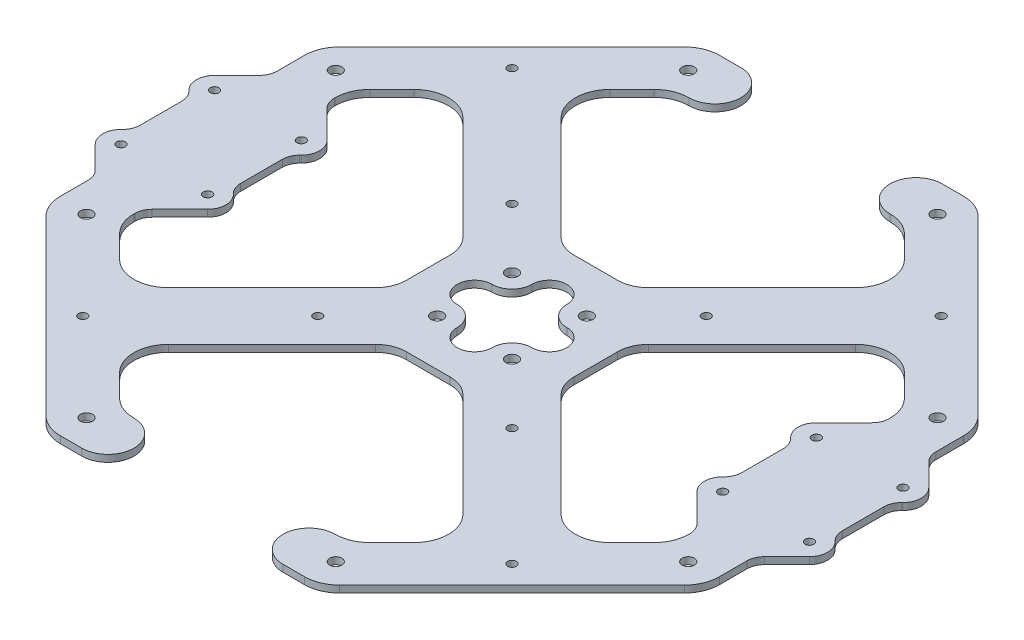
SolidWorks part; units mm, degrees
material "Hexcel AS4C (3000 Filaments)"
ref_plane "Front Plane" through (0, 0, 0) normal (0, 0, 1) x (1, 0, 0)
ref_plane "Top Plane" through (0, 0, 0) normal (0, 1, 0) x (1, 0, 0)
ref_plane "Right Plane" through (0, 0, 0) normal (1, 0, 0) x (0, 0, -1)
sketch "Sketch2" plane through (0, 0, 0) normal (0, 1, 0) x (1, 0, 0)
  line L0 (42.4264, 70.7107) -> (36.066, 77.0711)
  line L1 (92.0711, 42.2792) -> (42.2792, 92.0711)
  line L2 (35.2082, 95) -> (-35.2082, 95)
  line L3 (-42.2792, 92.0711) -> (-92.0711, 42.2792)
  line L5 (-92.0711, -42.2792) -> (-42.2792, -92.0711)
  line L6 (-35.2082, -95) -> (35.2082, -95)
  line L7 (42.2792, -92.0711) -> (92.0711, -42.2792)
  line L8 (95, 27.2345) -> (95, 35.2082)
  line L9 (28.9949, 80) -> (-28.9949, 80)
  line L10 (-70.7107, 42.4264) -> (-77.0711, 36.066)
  line L12 (-42.4264, -70.7107) -> (-36.066, -77.0711)
  line L13 (-28.9949, -80) -> (28.9949, -80)
  line L14 (70.7107, -42.4264) -> (77.0711, -36.066)
  line L68 (-80, 33.1371) -> (-80, -33.1371) construction
  line L69 (-80, -33.1371) -> (-33.1371, -80) construction
  line L70 (-33.1371, -80) -> (33.1371, -80) construction
  line L71 (33.1371, -80) -> (80, -33.1371) construction
  line L72 (80, -33.1371) -> (80, 33.1371) construction
  line L73 (80, 33.1371) -> (33.1371, 80) construction
  line L74 (33.1371, 80) -> (-33.1371, 80) construction
  line L75 (-33.1371, 80) -> (-80, 33.1371) construction
  line L76 (-95, 39.3503) -> (-95, -39.3503) construction
  line L77 (-95, -39.3503) -> (-39.3503, -95) construction
  line L78 (-39.3503, -95) -> (39.3503, -95) construction
  line L79 (39.3503, -95) -> (95, -39.3503) construction
  line L80 (95, -39.3503) -> (95, 39.3503) construction
  line L81 (95, 39.3503) -> (39.3503, 95) construction
  line L82 (39.3503, 95) -> (-39.3503, 95) construction
  line L83 (-39.3503, 95) -> (-95, 39.3503) construction
  line L84 (-26.7774, 12.6353) -> (-56.5685, 42.4264)
  line L93 (-12.6353, 26.7774) -> (-42.4264, 56.5685)
  line L94 (26.7774, 12.6353) -> (56.5685, 42.4264)
  line L95 (12.6353, 26.7774) -> (42.4264, 56.5685)
  line L96 (12.6353, -26.7774) -> (42.4264, -56.5685)
  line L97 (26.7774, -12.6353) -> (56.5685, -42.4264)
  line L98 (-26.7774, -12.6353) -> (-56.5685, -42.4264)
  line L99 (-12.6353, -26.7774) -> (-42.4264, -56.5685)
  line L100 (-6.2731, 24.1421) -> (6.2731, 24.1421)
  line L101 (24.1421, 6.2731) -> (24.1421, -6.2731)
  line L102 (6.2731, -24.1421) -> (-6.2731, -24.1421)
  line L103 (-24.1421, -6.2731) -> (-24.1421, 6.2731)
  line L104 (-36.066, 77.0711) -> (-42.4264, 70.7107)
  line L105 (77.0711, 36.066) -> (70.7107, 42.4264)
  line L106 (36.066, -77.0711) -> (42.4264, -70.7107)
  line L107 (-77.0711, -36.066) -> (-70.7107, -42.4264)
  line L115 (97, 15.5) -> (99.2388, 15.5)
  line L116 (80, 28.9949) -> (80, 28.7569)
  line L118 (74.2388, 15.5) -> (78, 15.5)
  line L120 (72.2388, 6.0043) -> (72.2388, -6.0043)
  line L131 (-95, 35.2082) -> (-95, -35.2082) [skipped]
  line L132 (101.2388, 6.0043) -> (101.2388, -6.0043)
  line L133 (102.9511, 17.2123) -> (96.4645, 23.699)
  line L134 (95, -27.2345) -> (95, -35.2082)
  line L135 (70.5265, 17.2123) -> (78.5355, 25.2214)
  line L136 (102.9511, 9.7877) -> (102.7033, 9.5398)
  line L137 (70.5265, -9.7877) -> (70.7743, -9.5398)
  line L138 (70.5265, 9.7877) -> (70.7743, 9.5398)
  line L139 (102.9511, -9.7877) -> (102.7033, -9.5398)
  line L140 (70.5265, -17.2123) -> (78.5355, -25.2214)
  line L141 (102.9511, -17.2123) -> (96.4645, -23.699)
  line L142 (74.2388, -15.5) -> (78, -15.5)
  line L143 (80, -28.9949) -> (80, -28.7569)
  line L144 (97, -15.5) -> (99.2388, -15.5)
  line L145 (-95, -27.2345) -> (-95, -35.2082)
  line L146 (-95, 27.2345) -> (-95, 35.2082)
  line L147 (-97, -15.5) -> (-99.2388, -15.5)
  line L148 (-80, -28.9949) -> (-80, -28.7569)
  line L149 (-74.2388, -15.5) -> (-78, -15.5)
  line L150 (-102.9511, -17.2123) -> (-96.4645, -23.699)
  line L151 (-70.5265, -17.2123) -> (-78.5355, -25.2214)
  line L152 (-102.9511, -9.7877) -> (-102.7033, -9.5398)
  line L153 (-70.5265, 9.7877) -> (-70.7743, 9.5398)
  line L154 (-70.5265, -9.7877) -> (-70.7743, -9.5398)
  line L155 (-102.9511, 9.7877) -> (-102.7033, 9.5398)
  line L156 (-70.5265, 17.2123) -> (-78.5355, 25.2214)
  line L157 (-102.9511, 17.2123) -> (-96.4645, 23.699)
  line L158 (-74.2388, 15.5) -> (-78, 15.5)
  line L159 (-80, 28.9949) -> (-80, 28.7569)
  line L160 (-97, 15.5) -> (-99.2388, 15.5)
  line L161 (-101.2388, 6.0043) -> (-101.2388, -6.0043)
  line L162 (-72.2388, 6.0043) -> (-72.2388, -6.0043)
  line L163 (-5.0334, 10.7834) -> (-5.0334, 14.3954)
  line L164 (-10.7834, 5.0334) -> (-14.3954, 5.0334)
  line L166 (-10.7834, -5.0334) -> (-14.3954, -5.0334)
  line L168 (-5.0334, -10.7834) -> (-5.0334, -14.3954)
  line L170 (5.0334, -10.7834) -> (5.0334, -14.3954)
  line L172 (10.7834, -5.0334) -> (14.3954, -5.0334)
  line L174 (10.7834, 5.0334) -> (14.3954, 5.0334)
  line L176 (5.0334, 10.7834) -> (5.0334, 14.3954)
  arc A0 (95, -27.2345) -> (96.4645, -23.699) centre (100, -27.2345) cw
  arc A2 (-80, -28.9949) -> (-77.0711, -36.066) centre (-70, -28.9949) ccw
  arc A3 (-36.066, -77.0711) -> (-28.9949, -80) centre (-28.9949, -70) ccw
  arc A4 (28.9949, -80) -> (36.066, -77.0711) centre (28.9949, -70) ccw
  arc A5 (77.0711, -36.066) -> (80, -28.9949) centre (70, -28.9949) ccw
  arc A6 (77.0711, 36.066) -> (80, 28.9949) centre (70, 28.9949) cw
  arc A7 (36.066, 77.0711) -> (28.9949, 80) centre (28.9949, 70) ccw
  arc A8 (-28.9949, 80) -> (-36.066, 77.0711) centre (-28.9949, 70) ccw
  arc A9 (-77.0711, 36.066) -> (-80, 28.9949) centre (-70, 28.9949) ccw
  arc A10 (-95, -35.2082) -> (-92.0711, -42.2792) centre (-85, -35.2082) ccw
  arc A11 (-42.2792, -92.0711) -> (-35.2082, -95) centre (-35.2082, -85) ccw
  arc A12 (35.2082, -95) -> (42.2792, -92.0711) centre (35.2082, -85) ccw
  arc A13 (92.0711, -42.2792) -> (95, -35.2082) centre (85, -35.2082) ccw
  arc A14 (92.0711, 42.2792) -> (95, 35.2082) centre (85, 35.2082) cw
  arc A15 (42.2792, 92.0711) -> (35.2082, 95) centre (35.2082, 85) ccw
  arc A16 (-35.2082, 95) -> (-42.2792, 92.0711) centre (-35.2082, 85) ccw
  arc A17 (-92.0711, 42.2792) -> (-95, 35.2082) centre (-85, 35.2082) ccw
  arc A18 (-42.4264, -70.7107) -> (-42.4264, -56.5685) centre (-35.3553, -63.6396) cw
  arc A19 (70.7107, -42.4264) -> (56.5685, -42.4264) centre (63.6396, -35.3553) cw
  arc A20 (42.4264, 70.7107) -> (42.4264, 56.5685) centre (35.3553, 63.6396) cw
  arc A21 (-70.7107, 42.4264) -> (-56.5685, 42.4264) centre (-63.6396, 35.3553) cw
  arc A22 (-56.5685, -42.4264) -> (-70.7107, -42.4264) centre (-63.6396, -35.3553) cw
  arc A23 (42.4264, -56.5685) -> (42.4264, -70.7107) centre (35.3553, -63.6396) cw
  arc A24 (56.5685, 42.4264) -> (70.7107, 42.4264) centre (63.6396, 35.3553) cw
  arc A25 (-42.4264, 56.5685) -> (-42.4264, 70.7107) centre (-35.3553, 63.6396) cw
  arc A26 (-12.6353, -26.7774) -> (-6.2731, -24.1421) centre (-6.2731, -33.1396) cw
  arc A27 (12.6353, -26.7774) -> (6.2731, -24.1421) centre (6.2731, -33.1396) ccw
  arc A28 (26.7774, -12.6353) -> (24.1421, -6.2731) centre (33.1396, -6.2731) cw
  arc A29 (26.7774, 12.6353) -> (24.1421, 6.2731) centre (33.1396, 6.2731) ccw
  arc A30 (12.6353, 26.7774) -> (6.2731, 24.1421) centre (6.2731, 33.1396) cw
  arc A31 (-12.6353, 26.7774) -> (-6.2731, 24.1421) centre (-6.2731, 33.1396) ccw
  arc A32 (-26.7774, -12.6353) -> (-24.1421, -6.2731) centre (-33.1396, -6.2731) ccw
  arc A33 (-26.7774, 12.6353) -> (-24.1421, 6.2731) centre (-33.1396, 6.2731) cw
  circle A34 centre (-86.7388, 35.9284) radius 1.75
  circle A35 centre (-35.9284, 86.7388) radius 1.75
  circle A36 centre (35.9284, 86.7388) radius 1.75
  circle A37 centre (86.7388, 35.9284) radius 1.75
  circle A38 centre (86.7388, -35.9284) radius 1.75
  circle A39 centre (35.9284, -86.7388) radius 1.75
  circle A40 centre (-35.9284, -86.7388) radius 1.75
  circle A41 centre (-86.7388, -35.9284) radius 1.75
  circle A42 centre (10.7834, 10.7834) radius 1.75
  circle A43 centre (10.7834, -10.7834) radius 1.75
  circle A44 centre (-10.7834, -10.7834) radius 1.75
  circle A45 centre (-10.7834, 10.7834) radius 1.75
  circle A55 centre (-28, 28) radius 1.25
  circle A56 centre (-61.8718, 61.8718) radius 1.25
  circle A57 centre (61.8718, 61.8718) radius 1.25
  circle A58 centre (28, 28) radius 1.25
  circle A59 centre (61.8718, -61.8718) radius 1.25
  circle A60 centre (28, -28) radius 1.25
  circle A61 centre (-61.8718, -61.8718) radius 1.25
  circle A62 centre (-28, -28) radius 1.25
  arc A63 (-28.9949, 80) -> (-28.9949, 95) centre (-28.9949, 87.5) ccw
  arc A64 (28.9949, 80) -> (28.9949, 95) centre (28.9949, 87.5) cw
  arc A65 (28.9949, -95) -> (28.9949, -80) centre (28.9949, -87.5) cw
  arc A66 (-28.9949, -95) -> (-28.9949, -80) centre (-28.9949, -87.5) ccw
  circle A71 centre (74.2388, 13.5) radius 1.25
  circle A72 centre (99.2388, 13.5) radius 1.25
  arc A77 (101.2388, 13.5) -> (99.2388, 15.5) centre (99.2388, 13.5) ccw
  arc A78 (72.2388, 13.5) -> (74.2388, 15.5) centre (74.2388, 13.5) cw
  arc A80 (97, 15.5) -> (95, 17.5) centre (97, 17.5) cw
  arc A81 (80, 17.5) -> (78, 15.5) centre (78, 17.5) cw
  circle A95 centre (74.2388, 13.5) radius 5.25
  circle A97 centre (99.2388, 13.5) radius 5.25
  arc A99 (72.2388, 6.0043) -> (70.7743, 9.5398) centre (67.2388, 6.0043) ccw
  arc A100 (78.5355, 25.2214) -> (80, 28.7569) centre (75, 28.7569) ccw
  arc A101 (101.2388, 6.0043) -> (102.7033, 9.5398) centre (106.2388, 6.0043) cw
  arc A102 (95, 27.2345) -> (96.4645, 23.699) centre (100, 27.2345) ccw
  arc A103 (101.2388, -6.0043) -> (102.7033, -9.5398) centre (106.2388, -6.0043) ccw
  arc A104 (78.5355, -25.2214) -> (80, -28.7569) centre (75, -28.7569) cw
  arc A105 (72.2388, -6.0043) -> (70.7743, -9.5398) centre (67.2388, -6.0043) cw
  circle A106 centre (99.2388, -13.5) radius 5.25
  circle A107 centre (74.2388, -13.5) radius 5.25
  arc A108 (80, -17.5) -> (78, -15.5) centre (78, -17.5) ccw
  arc A109 (97, -15.5) -> (95, -17.5) centre (97, -17.5) ccw
  arc A110 (72.2388, -13.5) -> (74.2388, -15.5) centre (74.2388, -13.5) ccw
  arc A111 (101.2388, -13.5) -> (99.2388, -15.5) centre (99.2388, -13.5) cw
  circle A112 centre (99.2388, -13.5) radius 1.25
  circle A113 centre (74.2388, -13.5) radius 1.25
  circle A114 centre (-74.2388, -13.5) radius 1.25
  circle A115 centre (-99.2388, -13.5) radius 1.25
  arc A116 (-101.2388, -13.5) -> (-99.2388, -15.5) centre (-99.2388, -13.5) ccw
  arc A117 (-72.2388, -13.5) -> (-74.2388, -15.5) centre (-74.2388, -13.5) cw
  arc A118 (-97, -15.5) -> (-95, -17.5) centre (-97, -17.5) cw
  arc A119 (-80, -17.5) -> (-78, -15.5) centre (-78, -17.5) cw
  circle A120 centre (-74.2388, -13.5) radius 5.25
  circle A121 centre (-99.2388, -13.5) radius 5.25
  arc A122 (-72.2388, -6.0043) -> (-70.7743, -9.5398) centre (-67.2388, -6.0043) ccw
  arc A123 (-78.5355, -25.2214) -> (-80, -28.7569) centre (-75, -28.7569) ccw
  arc A124 (-101.2388, -6.0043) -> (-102.7033, -9.5398) centre (-106.2388, -6.0043) cw
  arc A125 (-95, 27.2345) -> (-96.4645, 23.699) centre (-100, 27.2345) cw
  arc A126 (-101.2388, 6.0043) -> (-102.7033, 9.5398) centre (-106.2388, 6.0043) ccw
  arc A127 (-78.5355, 25.2214) -> (-80, 28.7569) centre (-75, 28.7569) cw
  arc A128 (-72.2388, 6.0043) -> (-70.7743, 9.5398) centre (-67.2388, 6.0043) cw
  circle A129 centre (-99.2388, 13.5) radius 5.25
  circle A130 centre (-74.2388, 13.5) radius 5.25
  arc A131 (-80, 17.5) -> (-78, 15.5) centre (-78, 17.5) ccw
  arc A132 (-97, 15.5) -> (-95, 17.5) centre (-97, 17.5) ccw
  arc A133 (-72.2388, 13.5) -> (-74.2388, 15.5) centre (-74.2388, 13.5) ccw
  arc A134 (-101.2388, 13.5) -> (-99.2388, 15.5) centre (-99.2388, 13.5) cw
  circle A135 centre (-99.2388, 13.5) radius 1.25
  circle A136 centre (-74.2388, 13.5) radius 1.25
  arc A137 (-95, -27.2345) -> (-96.4645, -23.699) centre (-100, -27.2345) ccw
  arc A139 (-5.0334, 10.7834) -> (-10.7834, 5.0334) centre (-10.7834, 10.7834) cw
  arc A140 (-10.7834, -5.0334) -> (-5.0334, -10.7834) centre (-10.7834, -10.7834) cw
  arc A141 (5.0334, -10.7834) -> (10.7834, -5.0334) centre (10.7834, -10.7834) cw
  arc A142 (10.7834, 5.0334) -> (5.0334, 10.7834) centre (10.7834, 10.7834) cw
  arc A143 (-5.0334, 10.7834) -> (5.0334, 10.7834) centre (0, 10.7834) cw
  arc A144 (10.7834, 5.0334) -> (10.7834, -5.0334) centre (10.7834, 0) cw
  arc A145 (5.0334, -10.7834) -> (-5.0334, -10.7834) centre (0, -10.7834) cw
  arc A146 (-10.7834, 5.0334) -> (-10.7834, -5.0334) centre (-10.7834, 0) ccw
  point P22 (0, 0)
  point P25 (0, 0)
  point P49 (0, 0)
  point P96 (0, 0)
  point P104 (-49.4975, 63.6396)
  point P105 (0, 0)
  point P142 (0, 0)
  point P150 (0, 0)
  point P159 (0, 0)
  point P169 (0, 0)
  point P187 (0, 0)
  point P204 (0, 0)
  dimension "D2" = 10
  dimension "D4" = 10
  dimension "D5" = 10
  dimension "D6" = 8.9974
  dimension "D7" = 4
  dimension "D9" = 4
  dimension "D11" = 8
  dimension "D14" = 2
  dimension "D15" = 2
  dimension "D16" = 4
  dimension "D17" = 5
  dimension "D18" = 5
  dimension "D3" = 4
  dimension "D1" = 15
  dimension "D10" = 4
extrude "Boss-Extrude1" add sketch "Sketch2" along normal blind 2
